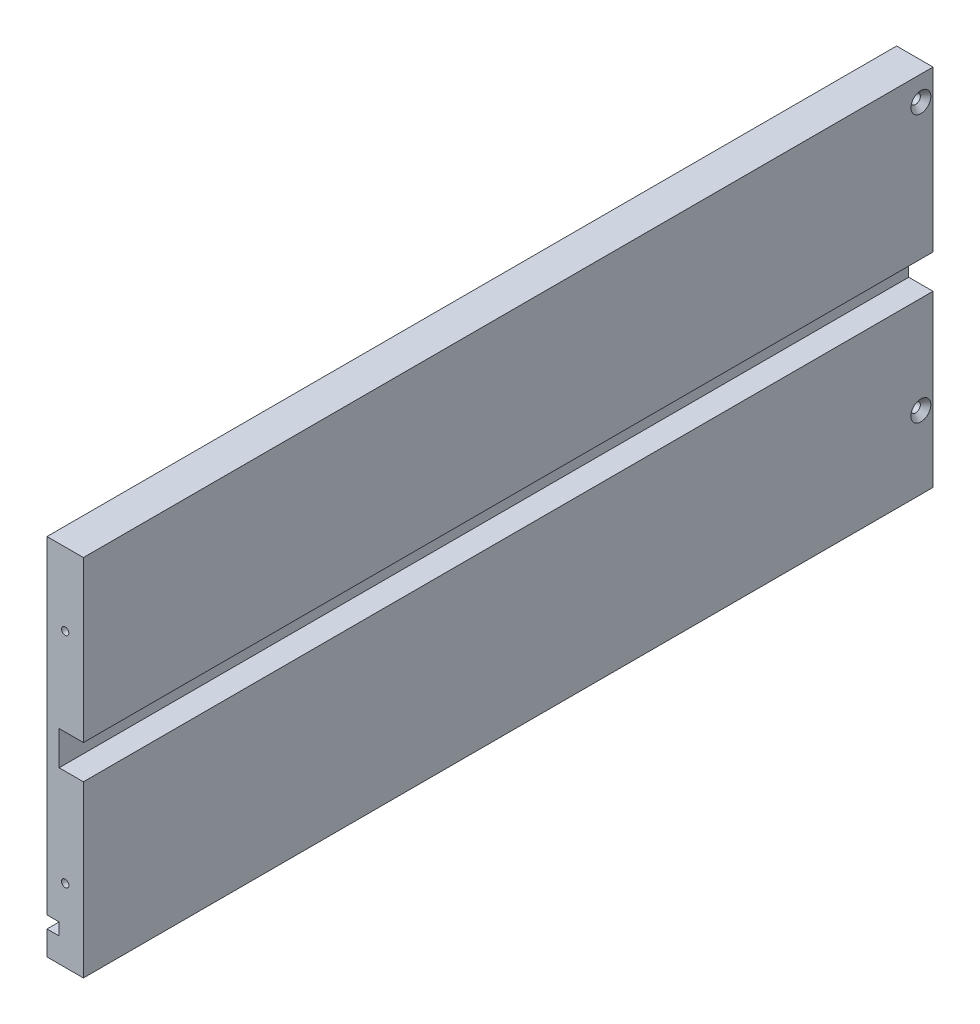
SolidWorks part; units mm, degrees
ref_plane "Front" through (0, 0, 0) normal (0, 0, 1) x (1, 0, 0)
ref_plane "Top" through (0, 0, 0) normal (0, 1, 0) x (1, 0, 0)
ref_plane "Right" through (0, 0, 0) normal (1, 0, 0) x (0, 0, -1)
sketch "Sketch2" plane through (0, 0, 0) normal (1, 0, 0) x (0, 0, -1)
  line L1 (0, 0) -> (350, 0)
  line L2 (0, 0) -> (0, 150)
  line L3 (0, 150) -> (350, 150)
  line L4 (350, 0) -> (350, 150)
  dimension "D1" = 350
  dimension "D2" = 150
extrude "Base-Extrude" add sketch "Sketch2" against normal blind 15
sketch "Sketch3" plane through (0, 0, 0) normal (0, 0, 1) x (1, 0, 0)
  line L0 (0, 150) -> (0, 0) construction
  line L1 (0, 70) -> (-10, 70)
  line L2 (0, 70) -> (0, 84)
  line L3 (0, 84) -> (-10, 84)
  line L4 (-10, 70) -> (-10, 84)
  line L5 (-15, 0) -> (0, 0) construction
  dimension "D1" = 70
  dimension "D2" = 10
  dimension "D3" = 14
extrude "Cut-Extrude1" cut sketch "Sketch3" against normal through all
sketch "Sketch4" plane through (0, 0, 0) normal (0, 0, 1) x (1, 0, 0)
  line L0 (-15, 150) -> (-15, 0) construction
  line L1 (-15, 10) -> (-10, 10)
  line L2 (-15, 10) -> (-15, 15)
  line L3 (-15, 15) -> (-10, 15)
  line L4 (-10, 10) -> (-10, 15)
  line L5 (-15, 0) -> (0, 0) construction
  dimension "D1" = 10
  dimension "D2" = 5
  dimension "D3" = 5
extrude "Cut-Extrude2" cut sketch "Sketch4" against normal through all
hole_wizard "CSK for M3.5 Flat Head Machine Screw1" positions "Sketch7" profile "Sketch6" countersink size "M3.5" standard "Ansi Metric" end condition through all
sketch "Sketch7" plane through (0, 0, 0) normal (1, 0, 0) x (0, 0, -1)
  line L0 (350, 84) -> (350, 150) construction
  line L1 (350, 150) -> (0, 150) construction
  line L2 (0, 0) -> (350, 0) construction
  point P0 (345, 140)
  point P5 (345, 30)
  dimension "D1" = 5
  dimension "D2" = 10
  dimension "D3" = 30
sketch "Sketch6" plane through (0, 140, -345) normal (0, 1, 0) x (0, 0, -1)
  line L0 (0, 0) -> (0, 15)
  line L1 (0, 15) -> (1.95, 15)
  line L2 (1.95, 15) -> (1.95, 2.15)
  line L3 (1.95, 2.15) -> (4.1, 0)
  line L5 (4.1, 0) -> (0, 0)
  line L6 (-1.95, 2.15) -> (-4.1, 0) construction
  line L11 (0, -6.35) -> (0, 107.95) construction
  dimension "Thru Hole Dia." = 3.9
  dimension "Thru Hole Depth" = 15
  dimension "Near C'Sink Dia." = 8.2
  dimension "Near C'Sink Angle" = 90
hole_wizard "M3.0 (3.000000) Diameter Hole1" positions "Sketch10" profile "Sketch9" hole size "M3.0" standard "Ansi Metric"
sketch "Sketch10" plane through (0, 0, 0) normal (0, 0, 1) x (1, 0, 0)
  line L0 (-7.5, 150) -> (-7.5, 0) construction
  line L1 (-15, 150) -> (0, 150) construction
  line L2 (-15, 0) -> (0, 0) construction
  point P0 (-7.5, 30)
  point P5 (-7.5, 120)
  dimension "D1" = 30
  dimension "D2" = 30
sketch "Sketch9" plane through (-7.5, 30, 0) normal (1, 0, 0) x (0, -1, 0)
  line L0 (0, 0) -> (0, 10.9013)
  line L1 (0, 10.9013) -> (1.5, 10)
  line L2 (1.5, 10) -> (1.5, 0)
  line L5 (1.5, 0) -> (0, 0)
  line L10 (0, 10.9013) -> (-1.5, 10) construction
  line L11 (0, -6.35) -> (0, 107.95) construction
  dimension "Hole Dia." = 3
  dimension "Hole Depth" = 10
  dimension "Drill Angle" = 118
